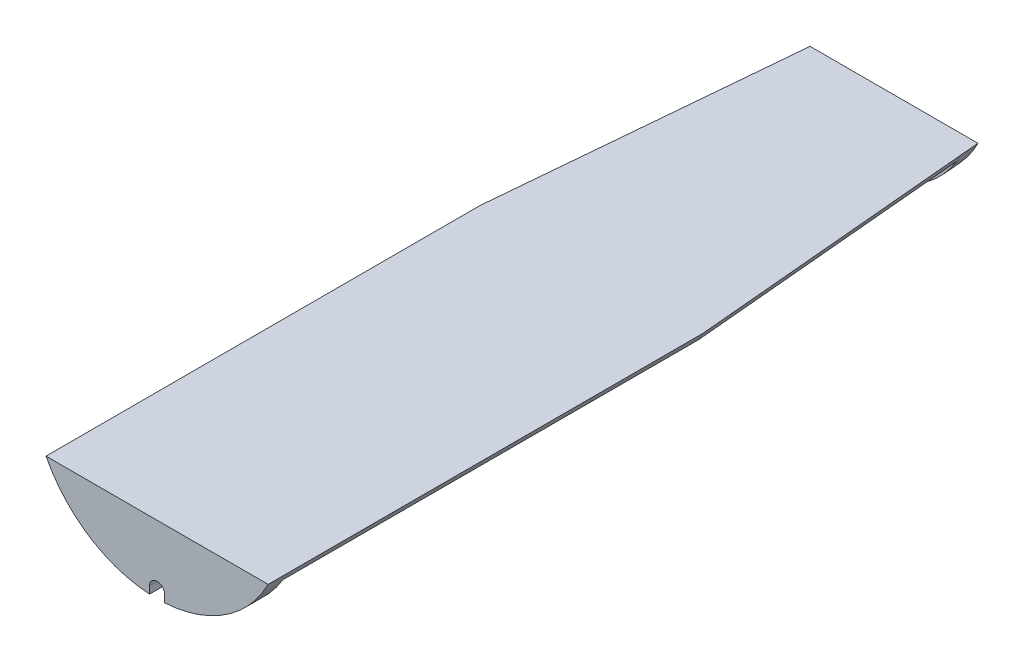
SolidWorks part; units mm, degrees
material "LW-PLA"
ref_plane "Front Plane" through (0, 0, 0) normal (0, 0, 1) x (1, 0, 0)
ref_plane "Top Plane" through (0, 0, 0) normal (0, 1, 0) x (1, 0, 0)
ref_plane "Right Plane" through (0, 0, 0) normal (1, 0, 0) x (0, 0, -1)
sketch "Sketch1" plane through (0, 0, 0) normal (0, 0, 1) x (1, 0, 0)
  line L4 (29.3939, 0) -> (-29.3939, 0)
  line L5 (-2, -17.9393) -> (-2, -16)
  line L6 (2, -16) -> (2, -17.9393)
  arc A3 (2, -17.9393) -> (29.3939, 0) centre (0, 15) ccw
  arc A4 (-29.3939, 0) -> (-2, -17.9393) centre (0, 15) ccw
  arc A5 (2, -16) -> (-2, -16) centre (0, -16) ccw
extrude "Boss-Extrude1" add sketch "Sketch1" against normal blind 5
ref_plane "Plane1" through (0, 0, -150) normal (0, 0, -1) x (-1, 0, 0)
ref_plane "Plane2" through (0, 0, -155) normal (0, 0, -1) x (-1, 0, 0)
sketch "Sketch4" plane through (0, 0, -5) normal (0, 0, -1) x (-1, 0, 0)
  line L4 (-28.2843, -2) -> (28.2843, -2)
  line L10 (-2, -17.9393) -> (-2, -16)
  line L15 (2, -16) -> (2, -17.9393)
  line L21 (29.3939, 0) -> (-29.3939, 0)
  line L22 (29.3939, 0) -> (-29.3939, 0)
  arc A3 (-29.3939, 0) -> (-2, -17.9393) centre (0, 15) ccw
  arc A4 (-29.3939, 0) -> (-28.2843, -2) centre (0, 15) ccw
  arc A12 (2, -16) -> (-2, -16) centre (0, -16) ccw
  arc A17 (2, -17.9393) -> (29.3939, 0) centre (0, 15) ccw
  arc A18 (28.2843, -2) -> (29.3939, 0) centre (0, 15) ccw
  dimension "D2" = 2
  dimension "D1" = 0
extrude "Boss-Extrude2" add sketch "Sketch4" along normal blind 110
sketch "Sketch6" plane through (0, 0, -115) normal (0, 0, -1) x (-1, 0, 0)
  line L2 (-28.2843, -2) -> (28.2843, -2)
  line L8 (-28.2843, -2) -> (28.2843, -2)
  line L10 (29.3939, 0) -> (-29.3939, 0)
  line L11 (29.3939, 0) -> (-29.3939, 0)
  arc A2 (-29.3939, 0) -> (-28.2843, -2) centre (0, 15) ccw
  arc A8 (-29.3939, 0) -> (-28.2843, -2) centre (0, 15) ccw
  arc A10 (28.2843, -2) -> (29.3939, 0) centre (0, 15) ccw
  arc A11 (28.2843, -2) -> (29.3939, 0) centre (0, 15) ccw
  dimension "D1" = 0
ref_plane "Plane6" through (0, 0, -190) normal (0, 0, -1) x (-1, 0, 0)
sketch "Sketch12" plane through (0, 0, -190) normal (0, 0, -1) x (-1, 0, 0)
  line L0 (22.6532, 0) -> (-22.6532, 0)
  line L1 (-2, -15.3054) -> (-2, -13.4173)
  line L2 (2, -13.4173) -> (2, -15.3054)
  ellipse E0 centre (0, -13.4173) end of major axis (0, -11.4162) minor radius 2 (2, -13.4173) -> (-2, -13.4173) ccw
  spline S0 degree 3 poles (2, -15.3054) (3.1177, -15.1805) (4.2108, -14.96) (6.3582, -14.3682) (7.4134, -13.9958) (9.4832, -13.1116) (10.4773, -12.6081) (12.3916, -11.4894) (13.3118, -10.8743) (15.08, -9.5355) (15.9283, -8.8113) (17.5504, -7.2533) (18.308, -6.4349) (20.4289, -3.8677) (21.6427, -2.0088) (22.6532, 0) knots 0 0 0 0 0.125 0.125 0.25 0.25 0.375 0.375 0.5 0.5 0.625 0.625 0.75 0.75 1 1 1 1
  spline S1 degree 3 poles (-22.6532, 0) (-22.149, -1.0023) (-21.3127, -2.456) (-20.3563, -3.8348) (-19.6916, -4.7372) (-19.3463, -5.1792) (-17.5671, -7.3271) (-15.9682, -8.8643) (-13.7403, -10.5496) (-13.2818, -10.8754) (-12.3514, -11.4953) (-11.8789, -11.79) (-10.4389, -12.6286) (-9.4494, -13.127) (-7.9187, -13.7794) (-7.4007, -13.9811) (-6.3484, -14.3507) (-5.812, -14.5191) (-4.1903, -14.965) (-3.1004, -15.1824) (-2, -15.3054) knots 0 0 0 0 0.125 0.1875 0.1875 0.25 0.25 0.5 0.5 0.5625 0.5625 0.625 0.625 0.75 0.75 0.8125 0.8125 0.875 0.875 1 1 1 1
ref_plane "Plane7" through (0, 0, -195) normal (0, 0, -1) x (-1, 0, 0)
sketch "Sketch13" plane through (0, 0, -195) normal (0, 0, -1) x (-1, 0, 0)
  line L0 (22.2349, 0) -> (-22.2349, 0)
  line L1 (-2, -15.1395) -> (-2, -13.256)
  line L2 (2, -13.256) -> (2, -15.1395)
  ellipse E0 centre (0, -13.256) end of major axis (0, -15.257) minor radius 2 (2, -13.256) -> (-2, -13.256) ccw
  spline S0 degree 3 poles (2, -15.1395) (3.0975, -15.012) (4.1705, -14.7891) (5.7513, -14.343) (6.2734, -14.1753) (7.3084, -13.804) (7.8227, -13.5997) (9.3416, -12.939) (10.3145, -12.4385) (12.188, -11.3285) (13.0886, -10.719) (14.8197, -9.3939) (15.6512, -8.6769) (17.2375, -7.1398) (17.9787, -6.3331) (20.0543, -3.804) (21.2434, -1.9747) (22.2349, 0) knots 0 0 0 0 0.125 0.125 0.1875 0.1875 0.25 0.25 0.375 0.375 0.5 0.5 0.625 0.625 0.75 0.75 1 1 1 1
  spline S1 degree 3 poles (-22.2349, 0) (-21.7403, -0.9851) (-20.9207, -2.4144) (-19.9847, -3.7708) (-19.3344, -4.6587) (-18.996, -5.0946) (-17.2533, -7.2126) (-15.6884, -8.73) (-13.5099, -10.3963) (-13.0615, -10.7188) (-12.15, -11.3337) (-11.687, -11.6263) (-10.2762, -12.4593) (-9.3068, -12.9553) (-7.8072, -13.6059) (-7.2998, -13.8072) (-6.2689, -14.1768) (-5.744, -14.3453) (-4.1514, -14.7939) (-3.0809, -15.0139) (-2, -15.1395) knots 0 0 0 0 0.125 0.1875 0.1875 0.25 0.25 0.5 0.5 0.5625 0.5625 0.625 0.625 0.75 0.75 0.8125 0.8125 0.875 0.875 1 1 1 1
loft "Loft4" add profiles "Sketch12", "Sketch13"
sketch "Sketch14" plane through (0, 0, -190) normal (0, 0, 1) x (1, 0, 0)
  line L0 (-21.5503, -2) -> (21.5498, -2)
  line L3 (-2, -15.3054) -> (-2, -13.4173)
  line L4 (2, -13.4173) -> (2, -15.3054)
  line L5 (22.6532, 0) -> (-22.6532, 0)
  line L8 (22.6532, 0) -> (-22.6532, 0)
  ellipse E1 centre (0, -13.4173) end of major axis (0, -11.4162) minor radius 2 (2, -13.4173) -> (-2, -13.4173) ccw
  spline S2 degree 3 poles (2153.3892, 2054.7793) (442.6758, 640.9393) (-97.6527, 89.6082) (-18.308, -6.4349) (-17.5504, -7.2533) (-15.9283, -8.8113) (-15.08, -9.5355) (-13.3118, -10.8743) (-12.3916, -11.4894) (-10.4773, -12.6081) (-9.4832, -13.1116) (-7.4134, -13.9958) (-6.3582, -14.3682) (47.2597, -29.1449) (146.267, 137.0177) (898.749, 2843.8171) knots -13.654352 -13.654352 -13.654352 -13.654352 0.25 0.25 0.375 0.375 0.5 0.5 0.625 0.625 0.75 0.75 0.875 0.875 6.992149 6.992149 6.992149 6.992149 only from (-22.6532, 0) to (-2, -15.3054)
  spline S3 degree 3 poles (-501.3336, 2939.4649) (-137.2223, 186.1273) (-53.1199, -30.7237) (5.812, -14.5191) (6.3484, -14.3507) (7.4007, -13.9811) (7.9187, -13.7794) (9.4494, -13.127) (10.4389, -12.6286) (11.8789, -11.79) (12.3514, -11.4953) (13.2818, -10.8754) (13.7403, -10.5496) (15.9682, -8.8643) (17.5671, -7.3271) (19.3463, -5.1792) (19.6916, -4.7372) (20.3563, -3.8348) (104.6431, 117.6817) (-744.3555, 820.1855) (-2258.8011, 1936.2844) knots -6.626246 -6.626246 -6.626246 -6.626246 0.125 0.125 0.1875 0.1875 0.25 0.25 0.375 0.375 0.4375 0.4375 0.5 0.5 0.75 0.75 0.8125 0.8125 0.875 17.336438 17.336438 17.336438 17.336438 only from (2, -15.3054) to (22.6532, 0)
  spline S4 degree 3 poles (-22.6532, 0) (-22.3091, -0.684) (-21.9414, -1.3506) (-21.5503, -2) knots 0 0 0 0 0.085128 0.085128 0.085128 0.085128
  spline S5 degree 3 poles (21.5498, -2) (21.9423, -1.3487) (22.3101, -0.682) (22.6532, 0) knots 0.914941 0.914941 0.914941 0.914941 1 1 1 1
  dimension "D2" = 2
  dimension "D1" = 0
sketch "Sketch15" plane through (0, 0, -115) normal (0, 0, -1) x (-1, 0, 0)
  line L2 (-28.2843, -2) -> (28.2843, -2)
  line L3 (29.3939, 0) -> (-29.3939, 0)
  line L4 (-28.2843, -2) -> (28.2843, -2)
  line L5 (29.3939, 0) -> (-29.3939, 0)
  arc A2 (-29.3939, 0) -> (-28.2843, -2) centre (0, 15) ccw
  arc A3 (28.2843, -2) -> (29.3939, 0) centre (0, 15) ccw
  arc A4 (-29.3939, 0) -> (-28.2843, -2) centre (0, 15) ccw
  arc A5 (28.2843, -2) -> (29.3939, 0) centre (0, 15) ccw
  dimension "D1" = 0
loft "Loft5" add profiles "Sketch15", "Sketch14"
